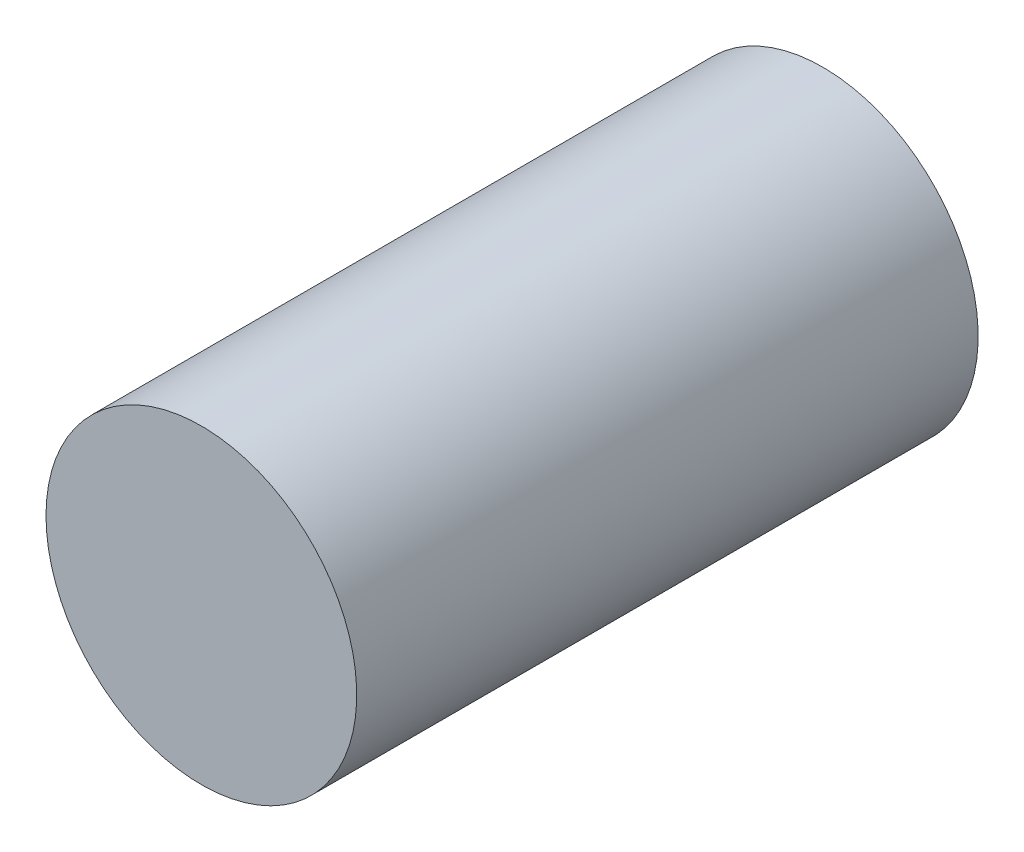
SolidWorks part; units mm, degrees
ref_plane "Front Plane" through (0, 0, 0) normal (1, 0, 0) x (0, 1, 0)
ref_plane "Top Plane" through (0, 0, 0) normal (0, 0, 1) x (0, 1, 0)
ref_plane "Right Plane" through (0, 0, 0) normal (0, 1, 0) x (-1, 0, 0)
sketch "Sketch2" plane through (0, 0, 0) normal (0, 0, 1) x (0, 1, 0)
  circle A0 centre (0, 0) radius 9.525
  dimension "D1" = 19.05
extrude "Boss-Extrude1" add sketch "Sketch2" along normal blind 38.1
